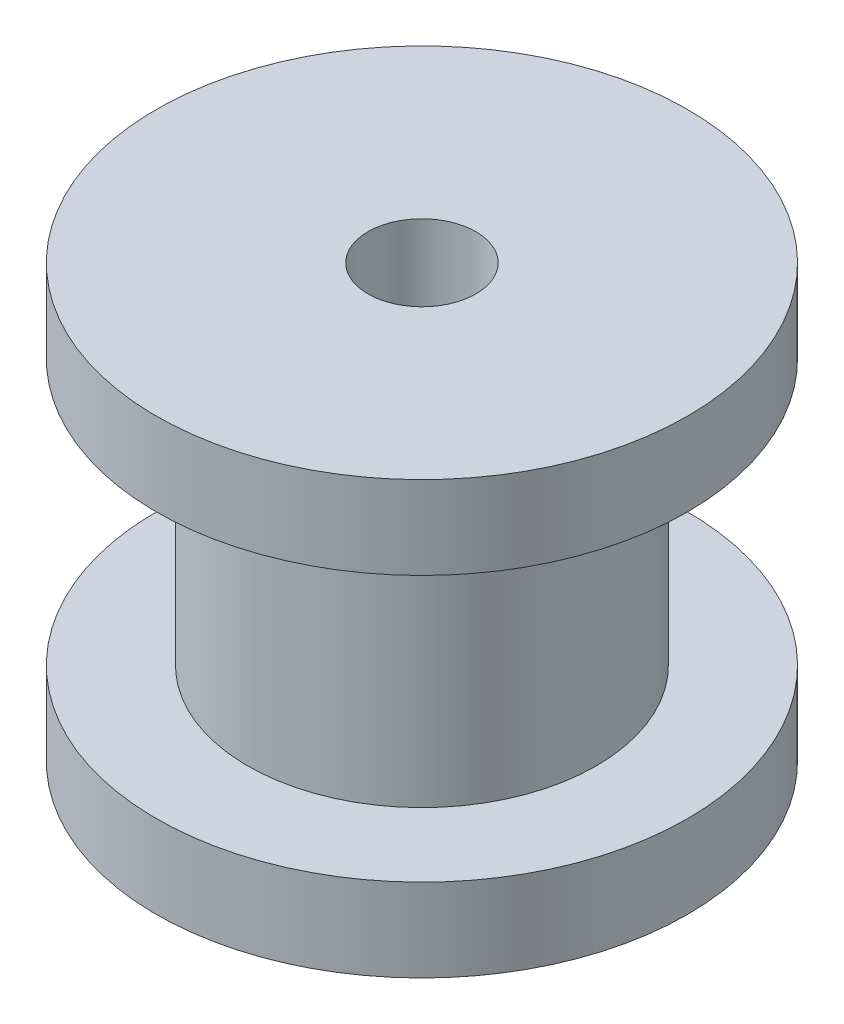
SolidWorks part; units mm, degrees
material "PLA"
ref_plane "Front Plane" through (0, 0, 0) normal (0, 0, 1) x (1, 0, 0)
ref_plane "Top Plane" through (0, 0, 0) normal (0, 1, 0) x (1, 0, 0)
ref_plane "Right Plane" through (0, 0, 0) normal (1, 0, 0) x (0, 0, -1)
sketch "Sketch1" plane through (0, 0, 0) normal (0, 0, 1) x (1, 0, 0)
  line L0 (0, -6.5) -> (0, 6.5)
  line L2 (5.25, 4) -> (5.25, -4)
  line L3 (5.25, -4) -> (8, -4)
  line L4 (8, -4) -> (8, -6.5)
  line L5 (8, -6.5) -> (0, -6.5)
  line L6 (5.25, 4) -> (8, 4)
  line L7 (8, 4) -> (8, 6.5)
  line L8 (8, 6.5) -> (0, 6.5)
  point P4 (0, 0)
  point P8 (0, 7.2277)
  dimension "D1" = 5.25
  dimension "D2" = 8
  dimension "D3" = 2.5
  dimension "D4" = 8
revolve "Revolve1" add sketch "Sketch1" angle 360 about L0
sketch "Sketch2" plane through (0, 6.5, 0) normal (0, 1, 0) x (1, 0, 0)
  circle A0 centre (0, 0) radius 1.625
  dimension "D1" = 3.25
extrude "Cut-Extrude1" cut sketch "Sketch2" against normal through all
